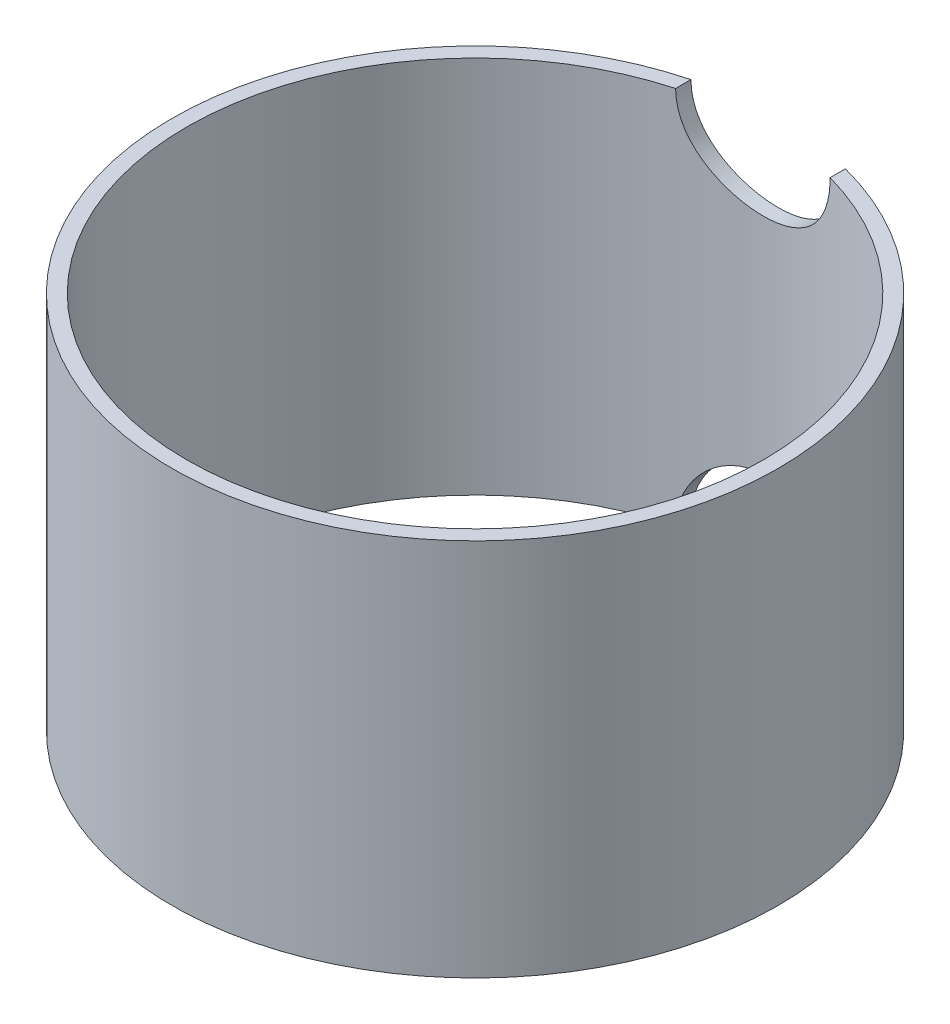
SolidWorks part; units mm, degrees
ref_plane "Front Plane" through (0, 0, 0) normal (0, 0, 1) x (1, 0, 0)
ref_plane "Top Plane" through (0, 0, 0) normal (0, 1, 0) x (1, 0, 0)
ref_plane "Right Plane" through (0, 0, 0) normal (1, 0, 0) x (0, 0, -1)
sketch "Sketch1" plane through (0, 0, 0) normal (0, 1, 0) x (1, 0, 0)
  circle A0 centre (0, 0) radius 41
  circle A1 centre (0, 0) radius 39
  dimension "D1" = 82
  dimension "D2" = 2
extrude "Boss-Extrude1" add sketch "Sketch1" along normal blind 51.2
sketch "Sketch2" plane through (0, 0, 0) normal (0, 0, 1) x (1, 0, 0)
  line L0 (41, 51.2) -> (-41, 51.2) construction
  circle A0 centre (0, 51.2) radius 10.45
  circle A1 centre (0, 0) radius 10.45
  dimension "D1" = 20.9
extrude "Cut-Extrude1" cut sketch "Sketch2" against normal through all
